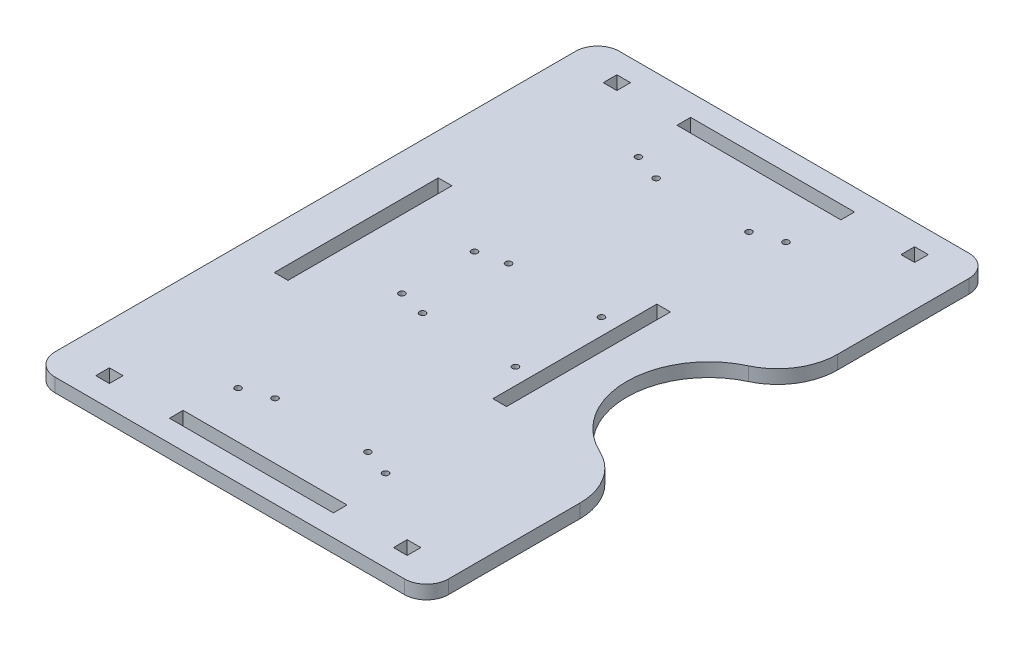
SolidWorks part; units mm, degrees
ref_plane "Front Plane" through (0, 0, 0) normal (0, 0, 1) x (1, 0, 0)
ref_plane "Top Plane" through (0, 0, 0) normal (0, 1, 0) x (1, 0, 0)
ref_plane "Right Plane" through (0, 0, 0) normal (1, 0, 0) x (0, 0, -1)
sketch "Sketch3" plane through (0, 0, 0) normal (0, 1, 0) x (1, 0, 0)
  line L4 (182.88, 0) -> (0, 0)
  line L5 (91.44, 262.3393) -> (91.44, 0) construction
  line L6 (19.05, 16.3877) -> (25.4, 16.3877)
  line L7 (19.05, 16.3877) -> (19.05, 10.0377)
  line L8 (19.05, 10.0377) -> (25.4, 10.0377)
  line L9 (25.4, 16.3877) -> (25.4, 10.0377)
  line L10 (163.83, 10.0377) -> (157.48, 10.0377)
  line L11 (157.48, 16.3877) -> (157.48, 10.0377)
  line L12 (163.83, 16.3877) -> (157.48, 16.3877)
  line L13 (163.83, 16.3877) -> (163.83, 10.0377)
  line L14 (0, 0) -> (0, 262.3393)
  line L15 (0, 262.3393) -> (182.88, 262.3393)
  line L16 (182.88, 262.3393) -> (182.88, 169.2696)
  line L17 (0, 131.1696) -> (179.6317, 131.1696) construction
  line L18 (163.83, 245.9515) -> (163.83, 252.3015)
  line L19 (163.83, 245.9515) -> (157.48, 245.9515)
  line L20 (157.48, 245.9515) -> (157.48, 252.3015)
  line L21 (163.83, 252.3015) -> (157.48, 252.3015)
  line L22 (19.05, 252.3015) -> (25.4, 252.3015)
  line L23 (25.4, 245.9515) -> (25.4, 252.3015)
  line L24 (19.05, 245.9515) -> (25.4, 245.9515)
  line L25 (19.05, 245.9515) -> (19.05, 252.3015)
  line L26 (182.88, 93.0696) -> (182.88, 0)
  line L27 (53.34, 252.3015) -> (129.54, 252.3015)
  line L28 (53.34, 16.3877) -> (129.54, 16.3877)
  line L29 (53.34, 16.3877) -> (53.34, 10.0377)
  line L30 (53.34, 10.0377) -> (129.54, 10.0377)
  line L31 (129.54, 16.3877) -> (129.54, 10.0377)
  line L32 (129.54, 245.9515) -> (129.54, 252.3015)
  line L33 (53.34, 245.9515) -> (129.54, 245.9515)
  line L34 (53.34, 245.9515) -> (53.34, 252.3015)
  line L35 (127, 93.0696) -> (120.65, 93.0696)
  line L40 (120.65, 169.2696) -> (120.65, 93.0696)
  line L41 (127, 169.2696) -> (120.65, 169.2696)
  line L42 (127, 169.2696) -> (127, 93.0696)
  line L44 (19.05, 169.2696) -> (25.4, 169.2696)
  line L45 (19.05, 169.2696) -> (19.05, 93.0696)
  line L46 (19.05, 93.0696) -> (25.4, 93.0696)
  line L47 (25.4, 169.2696) -> (25.4, 93.0696)
  circle A6 centre (57.15, 38.1) radius 1.4224
  circle A7 centre (57.15, 114.3) radius 1.4224
  circle A9 centre (125.73, 38.1) radius 1.4224
  circle A10 centre (69.85, 151.1577) radius 1.4224
  circle A11 centre (69.85, 219.7377) radius 1.4224
  circle A12 centre (113.03, 151.1577) radius 1.4224
  circle A13 centre (113.03, 219.7377) radius 1.4224
  circle A14 centre (113.03, 42.6016) radius 1.4224
  circle A15 centre (113.03, 111.1816) radius 1.4224
  circle A16 centre (69.85, 111.1816) radius 1.4224
  circle A17 centre (69.85, 42.6016) radius 1.4224
  circle A19 centre (125.73, 224.2393) radius 1.4224
  circle A20 centre (57.15, 224.2393) radius 1.4224
  circle A21 centre (57.15, 148.0393) radius 1.4224
  arc A22 (182.88, 169.2696) -> (182.88, 93.0696) centre (182.88, 131.1696) ccw
  dimension "D2" = 19.05
  dimension "D3" = 0
  dimension "D10" = 38.1
  dimension "D13" = 68.58
  dimension "D8" = 76.2
  dimension "D4" = 19.05
  dimension "D5" = 182.88
  dimension "D6" = 6.35
  dimension "D7" = 6.35
  dimension "D9" = 38.1
  dimension "D11" = 19.05
  dimension "D12" = 68.58
  dimension "D14" = 43.18
  dimension "D15" = 6.35
  dimension "D16" = 6.35
  dimension "D17" = 38.1
  dimension "D18" = 76.2
extrude "Boss-Extrude1" add sketch "Sketch3" along normal blind 6.35
fillet "Fillet1" radius 10.16 4 edges at (0, 3.175, 0) (0, 3.175, -262.3393) (182.88, 3.175, -262.3393) (182.88, 3.175, 0)
fillet "Fillet2" radius 27.94 2 edges at (182.88, 3.175, -169.2696) (182.88, 3.175, -93.0696)
